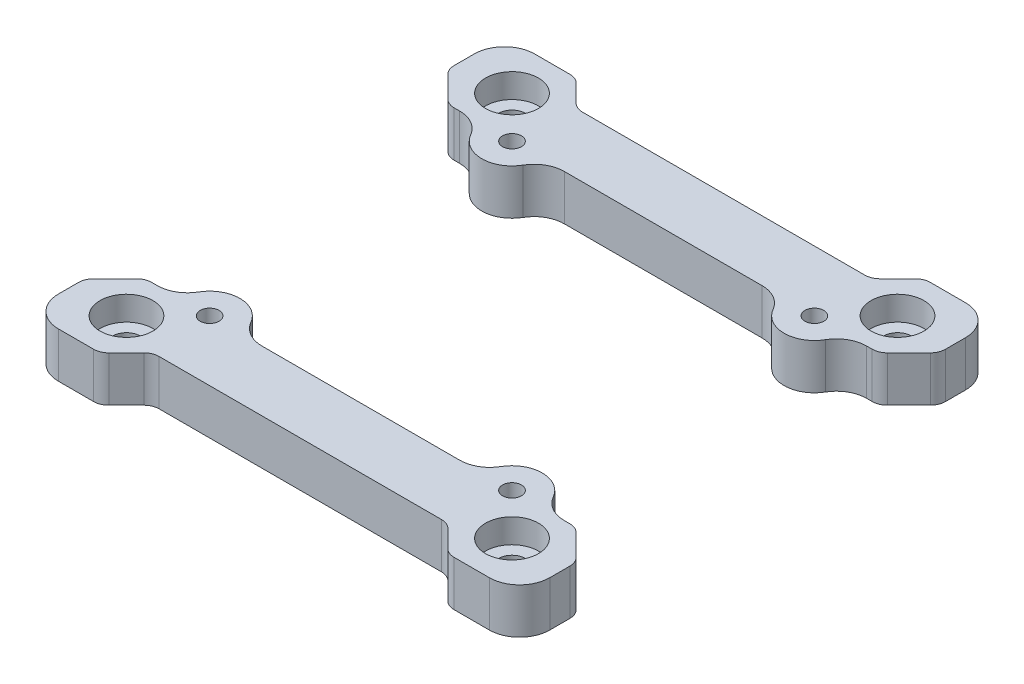
SolidWorks part; units mm, degrees
material "6061-T6 (SS)"
ref_plane "Front Plane" through (0, 0, 0) normal (0, 0, 1) x (1, 0, 0)
ref_plane "Top Plane" through (0, 0, 0) normal (0, 1, 0) x (1, 0, 0)
ref_plane "Right Plane" through (0, 0, 0) normal (1, 0, 0) x (0, 0, -1)
sketch "Sketch1" plane through (0, 0, 0) normal (0, 1, 0) x (1, 0, 0)
  line L0 (0, 0) -> (0, 12.75) construction
  line L1 (0, 0) -> (-12.75, 0) construction
  line L2 (9.7574, -1.25) -> (-9.7574, -1.25)
  line L3 (-9.7574, -1.25) -> (-11.5074, -3)
  line L4 (-11.5074, -3) -> (-16.25, -3)
  line L5 (-16.25, -3) -> (-16.25, 0.7426)
  line L6 (-16.25, 0.7426) -> (-14.2426, 2.75)
  line L7 (-14.2426, 2.75) -> (-12, 2.75)
  line L8 (-8, 2.75) -> (8, 2.75)
  line L9 (14.2426, 2.75) -> (12, 2.75)
  line L10 (16.25, 0.7426) -> (14.2426, 2.75)
  line L11 (16.25, -3) -> (16.25, 0.7426)
  line L12 (11.5074, -3) -> (16.25, -3)
  line L13 (9.7574, -1.25) -> (11.5074, -3)
  line L14 (0, 12.75) -> (-18.4956, 12.75) construction
  line L15 (0, 25.5) -> (-12.75, 25.5) construction
  line L16 (9.7574, 26.75) -> (11.5074, 28.5)
  line L17 (11.5074, 28.5) -> (16.25, 28.5)
  line L18 (16.25, 28.5) -> (16.25, 24.7574)
  line L19 (16.25, 24.7574) -> (14.2426, 22.75)
  line L20 (14.2426, 22.75) -> (12, 22.75)
  line L21 (-8, 22.75) -> (8, 22.75)
  line L22 (-14.2426, 22.75) -> (-12, 22.75)
  line L23 (-16.25, 24.7574) -> (-14.2426, 22.75)
  line L24 (-16.25, 28.5) -> (-16.25, 24.7574)
  line L25 (-11.5074, 28.5) -> (-16.25, 28.5)
  line L26 (-9.7574, 26.75) -> (-11.5074, 28.5)
  line L27 (9.7574, 26.75) -> (-9.7574, 26.75)
  arc A0 (-12, 2.75) -> (-8, 2.75) centre (-10, 2.75) cw
  circle A1 centre (-12.75, 0) radius 3 construction
  circle A2 centre (-10, 2.75) radius 0.8 construction
  arc A3 (12, 2.75) -> (8, 2.75) centre (10, 2.75) ccw
  circle A4 centre (-10, 22.75) radius 0.8 construction
  circle A5 centre (-12.75, 25.5) radius 3 construction
  arc A6 (12, 22.75) -> (8, 22.75) centre (10, 22.75) cw
  arc A7 (-12, 22.75) -> (-8, 22.75) centre (-10, 22.75) ccw
  point P22 (0, 2.75)
  point P30 (0, -1.25)
  point P45 (0, 26.75)
  point P46 (0, 22.75)
  point P47 (0, 0)
  dimension "D4" = 6
  dimension "D7" = 1.6
  dimension "D8" = 2
  dimension "D1" = 12.75
  dimension "D2" = 1.25
  dimension "D3" = 45
  dimension "D5" = 16.25
  dimension "D6" = 2.75
  dimension "D9" = 10
  dimension "D10" = 12.75
  dimension "D11" = 25.5
extrude "Boss-Extrude1" add sketch "Sketch1" along normal mid plane 3
fillet "Fillet1" radius 1 8 edges at (14.2426, 0, -2.75) (16.25, 0, -0.7426) (-14.2426, 0, -2.75) (-16.25, 0, -0.7426) (11.5074, 0, 3) (9.7574, 0, 1.25) (-11.5074, 0, 3) (-9.7574, 0, 1.25)
fillet "Fillet2" radius 2 6 edges at (-12, 0, -2.75) (-8, 0, -2.75) (8, 0, -2.75) (12, 0, -2.75) (16.25, 0, 3) (-16.25, 0, 3)
hole_wizard "CBORE for M1.6 SHCS1" positions "Sketch4" profile "Sketch3" counterbore size "M1.6" standard "ANSI Metric" end condition through all
sketch "Sketch4" plane through (0, 1.5, 0) normal (0, 1, 0) x (1, 0, 0)
  line L0 (0, 0) -> (0, 9.7579) construction
  line L1 (0, 0) -> (0, 12.75) construction
  point P0 (-12.75, 0)
  point P11 (12.75, 0)
  point P12 (-12.75, 25.5)
  point P16 (12.75, 25.5)
sketch "Sketch3" plane through (-12.75, 1.5, 0) normal (1, 0, 0) x (0, 0, 1)
  line L0 (0, 0) -> (0, 3)
  line L1 (0, 3) -> (0.9, 3)
  line L3 (0.9, 3) -> (0.9, 1.6)
  line L4 (0.9, 1.6) -> (1.75, 1.6)
  line L5 (1.75, 1.6) -> (1.75, 0)
  line L7 (1.75, 0) -> (0, 0)
  line L11 (0, -6.35) -> (0, 107.95) construction
  dimension "Thru Hole Dia." = 1.8
  dimension "Thru Hole Depth" = 3
  dimension "C'Bore Dia." = 3.5
  dimension "C'Bore Depth" = 1.6
hole_wizard "M1.6x0.35 Tapped Hole1" positions "Sketch5" profile "Sketch6" tap size "M1.6x0.35" standard "ANSI Metric" end condition through all
sketch "Sketch5" plane through (0, 1.5, 0) normal (0, 1, 0) x (1, 0, 0)
  line L0 (0, 0) -> (0, 16.9724) construction
  line L1 (0, 0) -> (0, 12.75) construction
  point P0 (-10, 2.75)
  point P12 (10, 2.75)
  point P13 (-10, 22.75)
  point P17 (10, 22.75)
sketch "Sketch6" plane through (-10, 1.5, -2.75) normal (1, 0, 0) x (0, 0, 1)
  line L0 (0, 0) -> (0, 3)
  line L1 (0, 3) -> (0.625, 3)
  line L2 (0.625, 3) -> (0.625, 0)
  line L5 (0.625, 0) -> (0, 0)
  line L11 (0, -6.35) -> (0, 107.95) construction
  dimension "Thru Tap Drill Dia." = 1.25
  dimension "Thru Tap Drill Depth" = 3
cosmetic thread "Hole Thread1" parameters "D2"=1.6
cosmetic thread "Hole Thread2" parameters "D2"=1.6
cosmetic thread "Hole Thread3" parameters "D2"=1.6
cosmetic thread "Hole Thread4" parameters "D2"=1.6
fillet "Fillet3" radius 1 8 edges at (16.25, 0, -24.7574) (14.2426, 0, -22.75) (11.5074, 0, -28.5) (9.7574, 0, -26.75) (-9.7574, 0, -26.75) (-11.5074, 0, -28.5) (-14.2426, 0, -22.75) (-16.25, 0, -24.7574)
fillet "Fillet4" radius 2 6 edges at (16.25, 0, -28.5) (12, 0, -22.75) (8, 0, -22.75) (-8, 0, -22.75) (-12, 0, -22.75) (-16.25, 0, -28.5)
